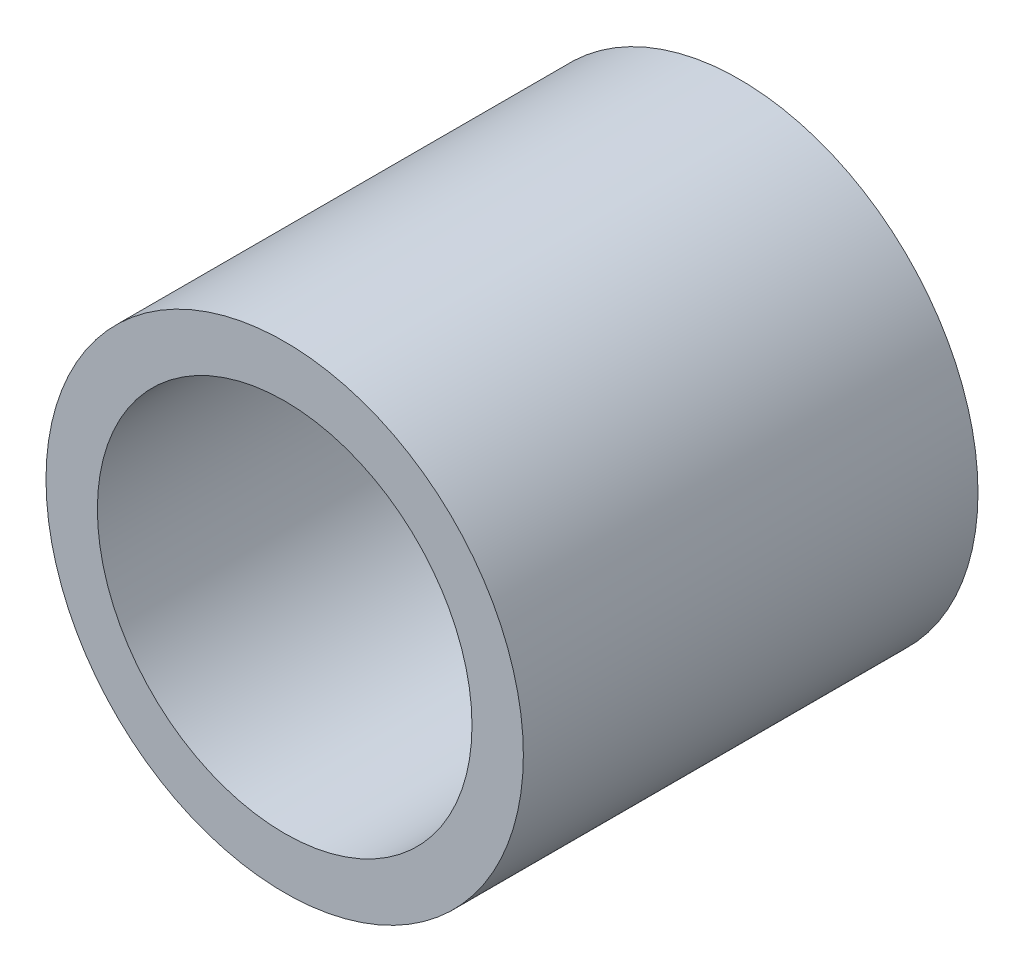
SolidWorks part; units mm, degrees
ref_plane "Front Plane" through (0, 0, 0) normal (0, 0, 1) x (1, 0, 0)
ref_plane "Top Plane" through (0, 0, 0) normal (0, 1, 0) x (1, 0, 0)
ref_plane "Right Plane" through (0, 0, 0) normal (1, 0, 0) x (0, 0, -1)
sketch "Sketch1" plane through (0, 0, 0) normal (0, 0, 1) x (1, 0, 0)
  circle A0 centre (0, 0) radius 10.4648
  circle A1 centre (0, 0) radius 13.335
  dimension "D1" = 2.8702
  dimension "D2" = 26.67
extrude "Boss-Extrude1" add sketch "Sketch1" along normal blind 25.4
